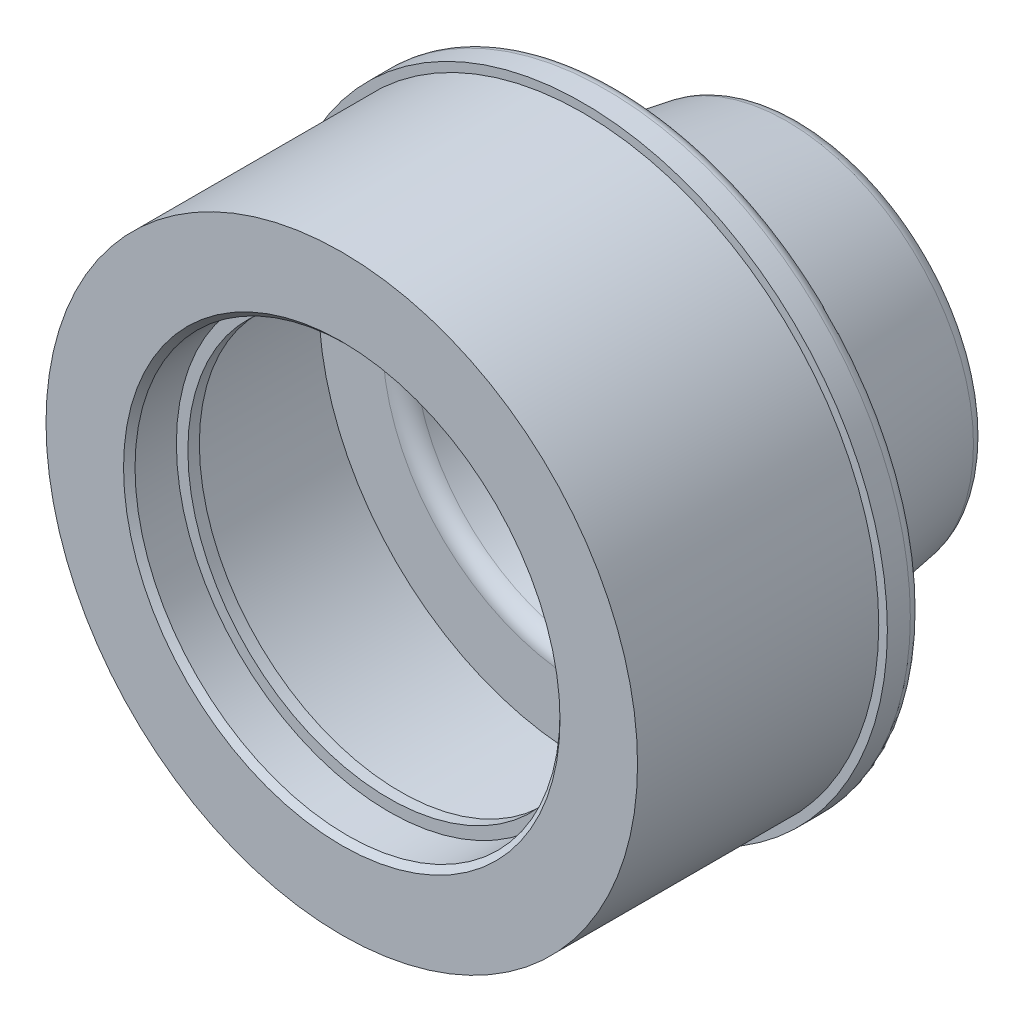
SolidWorks part; units mm, degrees
ref_plane "前视基准面" through (0, 0, 0) normal (0, 0, 1) x (1, 0, 0)
ref_plane "上视基准面" through (0, 0, 0) normal (0, 1, 0) x (1, 0, 0)
ref_plane "右视基准面" through (0, 0, 0) normal (1, 0, 0) x (0, 0, -1)
other "Configuration Table"
sketch "草图2" plane through (0, 0, 0) normal (1, 0, 0) x (0, 0, -1)
  line L0 (0, 0) -> (44.2254, 0) construction
  line L1 (0, 0) -> (3, 0)
  line L2 (3, 0) -> (3, 16.0362)
  line L6 (0, 13.5) -> (0, 0)
  line L8 (-16, 16.2) -> (-16, 26.5)
  line L9 (-16, 26.5) -> (-13, 26.5)
  line L10 (-13, 26.5) -> (-13, 18.7362)
  line L12 (-16, 16.2) -> (0, 13.5)
  line L13 (-13, 18.7362) -> (3, 16.0362)
  dimension "D1" = 3
  dimension "D2" = 3
  dimension "D3" = 27
  dimension "D4" = 53
  dimension "D5" = 19
  dimension "D6" = 3
  dimension "D7" = 2.7
revolve "旋转1" add sketch "草图2" angle 360 about L0
sketch "草图3" plane through (0, 0, -3) normal (0, 0, -1) x (-1, 0, 0)
  line L1 (-5.6569, 5.6569) -> (5.6569, 5.6569) construction
  line L2 (-5.6569, 5.6569) -> (-5.6569, -5.6569) construction
  line L3 (-5.6569, -5.6569) -> (5.6569, -5.6569) construction
  line L4 (5.6569, 5.6569) -> (5.6569, -5.6569) construction
  line L5 (-5.6569, 5.6569) -> (5.6569, -5.6569) construction
  line L6 (-5.6569, -5.6569) -> (5.6569, 5.6569) construction
  circle A0 centre (5.6569, 5.6569) radius 1.675
  circle A1 centre (5.6569, -5.6569) radius 1.675
  circle A2 centre (-5.6569, 5.6569) radius 1.675
  circle A3 centre (-5.6569, -5.6569) radius 1.675
  point P0 (0, 0)
  dimension "D1" = 3.35
  dimension "D2" = 16
extrude "切除-拉伸1" cut sketch "草图3" against normal blind 10
sketch "草图4" plane through (0, 0, 0) normal (0, 1, 0) x (1, 0, 0)
  line L0 (0, 3) -> (0, -8) construction
  line L4 (-13.5, 0) -> (13.5, 0) construction
  line L5 (16.0362, 3) -> (-16.0362, 3) construction
  circle A0 centre (0, -8) radius 1.75
  dimension "D1" = 3.5
  dimension "D2" = 8
extrude "切除-拉伸2" cut sketch "草图4" against normal through all
fillet "圆角1" radius 1.5 4 edges at (18.7362, 0, 13) (16.2, 0, 16) (13.5, 0, 0) (16.0362, 0, -3)
sketch "草图5" plane through (0, 0, 16) normal (0, 0, 1) x (1, 0, 0)
  circle A4 centre (0, 0) radius 25.75
  circle A5 centre (0, 0) radius 23
  dimension "D2" = 46
  dimension "D1" = 51.5
extrude "凸台-拉伸1" add sketch "草图5" along normal blind 21
sketch "草图7" plane through (0, 0, 37) normal (0, 0, 1) x (1, 0, 0)
  circle A0 centre (0, 0) radius 18.5
  circle A2 centre (0, 0) radius 25.75
  circle A3 centre (0, 0) radius 25.75 construction
  dimension "D1" = 37
  dimension "D2" = 51.5
extrude "凸台-拉伸2" add sketch "草图7" against normal blind 4.1
sketch "草图8" plane through (0, 0, 32.9) normal (0, 0, -1) x (-1, 0, 0)
  circle A0 centre (0, 0) radius 17.5
  circle A2 centre (0, 0) radius 25.75
  circle A3 centre (0, 0) radius 25.75 construction
  dimension "D1" = 35
extrude "凸台-拉伸3" add sketch "草图8" along normal blind 1
sketch "草图9" plane through (0, 0, 16) normal (0, 0, 1) x (1, 0, 0)
  line L0 (0, -32.344) -> (0, 32.344) construction
  line L1 (-1, 25.7306) -> (-1, 27.7306)
  line L2 (-1, 27.7306) -> (1, 27.7306)
  line L3 (1, 27.7306) -> (1, 25.7306)
  circle A0 centre (0, 0) radius 25.75 construction
  circle A1 centre (0, 0) radius 25.75
  point P6 (0, 0)
  circle M3 centre (0, 0) radius 25.75
  dimension "D1" = 2
  dimension "D2" = 2
extrude "凸台-拉伸4" [suppressed] add sketch "草图9" along normal offset from surface (16 mm away) 5 contours L0 L2 L1 M3 | L0 A1 L3 L2
pattern_circular "阵列(圆周)1" [suppressed] count 6 over 360
fillet "圆角2" radius 1 1 edges at (26.5, 0, 13)
chamfer "倒角1" distance 0.5 angle 45 1 edges at (18.5, 0, 37)
